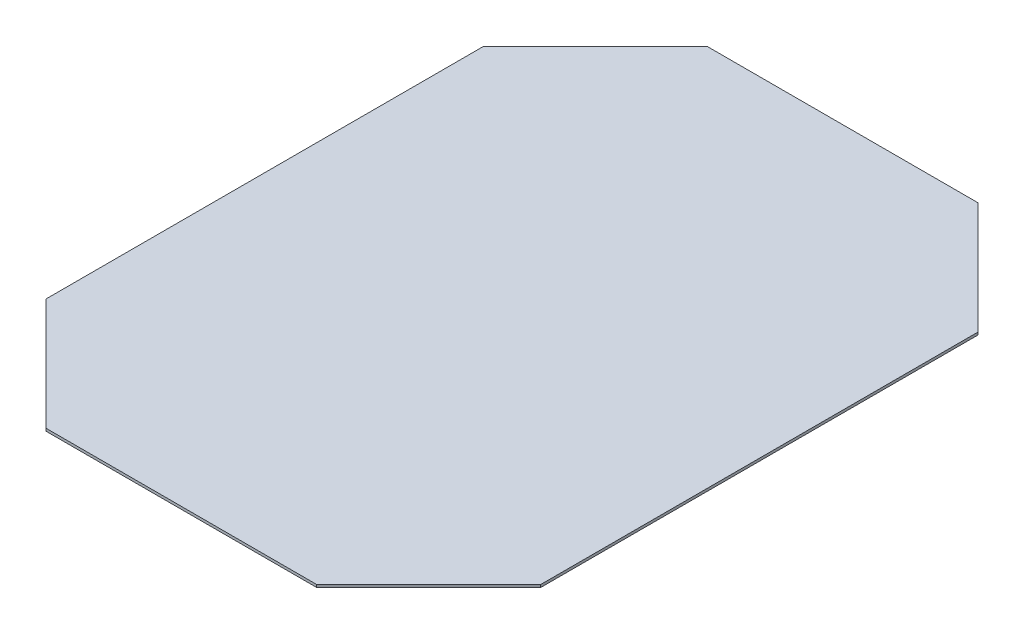
SolidWorks part; units mm, degrees
material "6061 Alloy"
ref_plane "Front Plane" through (0, 0, 0) normal (0, 0, 1) x (1, 0, 0)
ref_plane "Top Plane" through (0, 0, 0) normal (0, 1, 0) x (1, 0, 0)
ref_plane "Right Plane" through (0, 0, 0) normal (1, 0, 0) x (0, 0, -1)
sketch "Sketch1" plane through (0, 0, 0) normal (0, 1, 0) x (1, 0, 0)
  line L0 (-82.55, 201.6125) -> (82.55, 201.6125)
  line L1 (82.55, 201.6125) -> (150.8125, 133.35)
  line L2 (150.8125, 133.35) -> (150.8125, -133.35)
  line L3 (150.8125, -133.35) -> (82.55, -201.6125)
  line L4 (82.55, -201.6125) -> (-82.55, -201.6125)
  line L5 (-82.55, -201.6125) -> (-150.8125, -133.35)
  line L6 (-150.8125, -133.35) -> (-150.8125, 133.35)
  line L7 (-150.8125, 133.35) -> (-82.55, 201.6125)
  line L8 (0, -201.6125) -> (0, 201.6125) construction
  point P9 (0, 0)
  dimension "D1" = 266.7
  dimension "D2" = 266.7
  dimension "D3" = 135
  dimension "D4" = 135
  dimension "D5" = 135
  dimension "D6" = 135
  dimension "D7" = 165.1
  dimension "D8" = 165.1
  dimension "D9" = 403.225
extrude "Boss-Extrude1" add sketch "Sketch1" along normal blind 1.5875
equation "\"D3@Sketch1\"=135"
equation "\"D2@Sketch1\"=\"D1@Sketch1\""
equation "\"D8@Sketch1\"=\"D7@Sketch1\""
